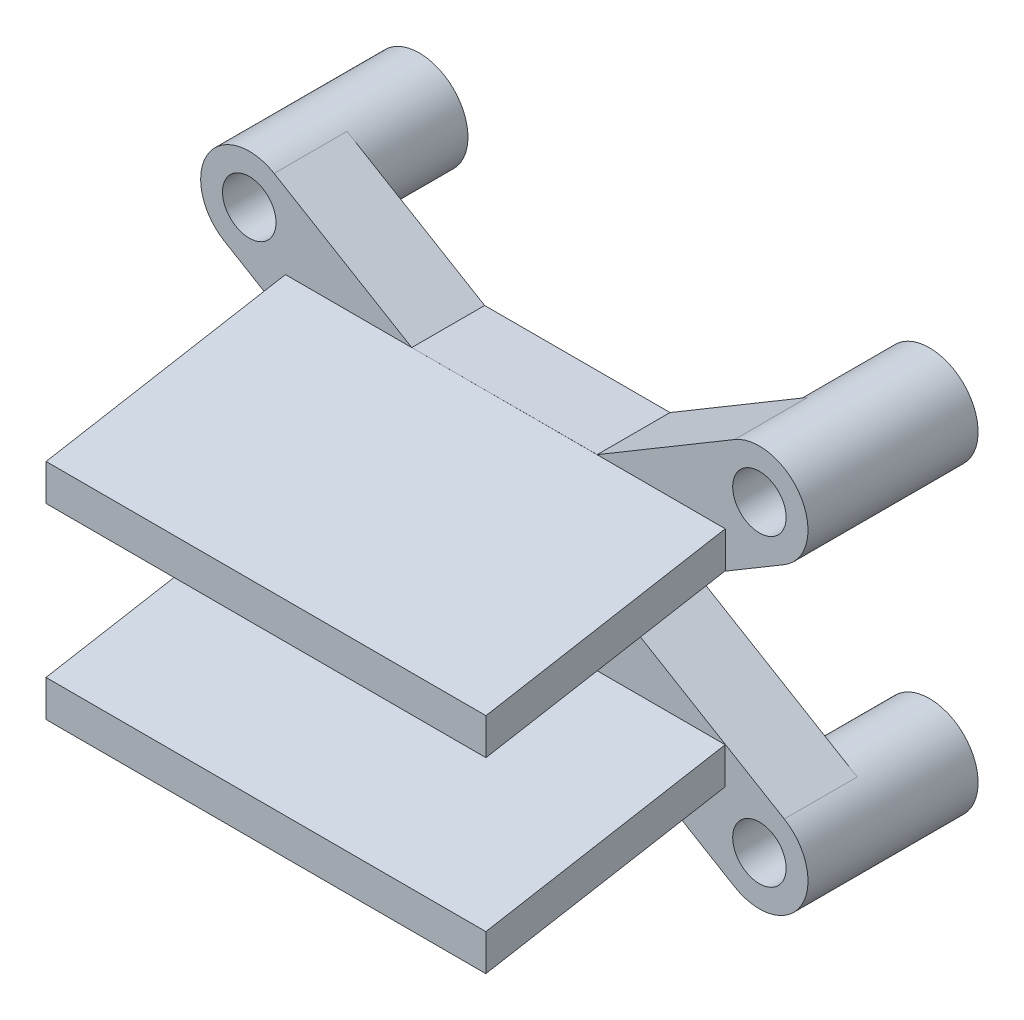
SolidWorks part; units mm, degrees
ref_plane "Alzado" through (0, 0, 0) normal (0, 0, 1) x (1, 0, 0)
ref_plane "Planta" through (0, 0, 0) normal (0, 1, 0) x (1, 0, 0)
ref_plane "Vista lateral" through (0, 0, 0) normal (1, 0, 0) x (0, 0, -1)
sketch "Croquis1" plane through (0, 0, 0) normal (0, 0, 1) x (1, 0, 0)
  line L0 (0, 0) -> (21, 0)
  line L1 (21, 0) -> (21, 12.5)
  line L2 (-1.023, 1.7186) -> (19.977, 14.2186)
  line L3 (1.0301, 14.2286) -> (22.0238, 1.7181)
  line L4 (22.023, 10.7814) -> (1.023, -1.7186)
  line L5 (19.9762, -1.7181) -> (-1.0176, 10.7924)
  circle A0 centre (0, 0) radius 2
  circle A1 centre (21, 12.5) radius 2
  circle A2 centre (21, 0) radius 2
  circle A3 centre (0.0063, 12.5105) radius 2
  circle A4 centre (0.0063, 12.5105) radius 1.1
  circle A5 centre (0, 0) radius 1.1
  circle A6 centre (21, 0) radius 1.1
  circle A7 centre (21, 12.5) radius 1.1
  dimension "D3" = 4
  dimension "D4" = 4
  dimension "D5" = 4
  dimension "D6" = 4
  dimension "D7" = 2.2
  dimension "D8" = 2.2
  dimension "D9" = 2.2
  dimension "D10" = 2.2
  dimension "D1" = 21
  dimension "D2" = 12.5
extrude "Saliente-Extruir1" add sketch "Croquis1" along normal blind 3
sketch "Croquis2" plane through (0, 0, 0) normal (0, 0, -1) x (-1, 0, 0)
  line L0 (-19.9762, -1.7181) -> (1.0176, 10.7924) construction
  line L1 (-22.023, 10.7814) -> (-1.023, -1.7186) construction
  line L2 (-1.0301, 14.2286) -> (-22.0238, 1.7181) construction
  line L3 (1.023, 1.7186) -> (-19.977, 14.2186) construction
  line L4 (0, 0) -> (-21, 0) construction
  line L5 (-21, 0) -> (-21, 12.5) construction
  line L6 (-19.9762, -1.7181) -> (1.0176, 10.7924)
  line L7 (-22.023, 10.7814) -> (-1.023, -1.7186)
  line L8 (-1.0301, 14.2286) -> (-22.0238, 1.7181)
  line L9 (1.023, 1.7186) -> (-19.977, 14.2186)
  line L10 (0, 0) -> (-21, 0)
  line L11 (-21, 0) -> (-21, 12.5)
  circle A1 centre (-0.0063, 12.5105) radius 2
  circle A2 centre (-0.0063, 12.5105) radius 2
  circle A3 centre (-21, 0) radius 2
  circle A4 centre (-21, 0) radius 2
  circle A5 centre (-21, 12.5) radius 2
  circle A6 centre (-21, 12.5) radius 2
  circle A7 centre (0, 0) radius 2
  circle A8 centre (0, 0) radius 2
  circle A9 centre (-21, 12.5) radius 1.1
  circle A10 centre (-21, 12.5) radius 1.1
  circle A11 centre (-21, 0) radius 1.1
  circle A12 centre (-21, 0) radius 1.1
  circle A13 centre (0, 0) radius 1.1
  circle A14 centre (0, 0) radius 1.1
  circle A15 centre (-0.0063, 12.5105) radius 1.1
  circle A16 centre (-0.0063, 12.5105) radius 1.1
  dimension "D1" = 0
  dimension "D2" = 0
  dimension "D3" = 0
  dimension "D4" = 0
  dimension "D5" = 0
  dimension "D6" = 0
  dimension "D7" = 0
  dimension "D8" = 0
extrude "Saliente-Extruir2" add sketch "Croquis2" along normal blind 4
sketch "Croquis3" plane through (0, 0, 3) normal (0, 0, 1) x (1, 0, 0)
  line L0 (19.9762, -1.7181) -> (-1.0176, 10.7924) construction
  line L1 (22.023, 10.7814) -> (1.023, -1.7186) construction
  line L2 (1.0301, 14.2286) -> (22.0238, 1.7181) construction
  line L3 (-1.023, 1.7186) -> (19.977, 14.2186) construction
  line L4 (0, 0) -> (21, 0) construction
  line L5 (21, 0) -> (21, 12.5) construction
  line L6 (19.9762, -1.7181) -> (-1.0176, 10.7924)
  line L7 (22.023, 10.7814) -> (1.023, -1.7186)
  line L8 (1.0301, 14.2286) -> (22.0238, 1.7181)
  line L9 (-1.023, 1.7186) -> (19.977, 14.2186)
  line L10 (0, 0) -> (21, 0)
  line L11 (21, 0) -> (21, 12.5)
  line L12 (14.4145, 6.2526) -> (6.5974, 6.2545) construction
  line L13 (6.5974, 6.2545) -> (10.506, 6.2536) construction
  line L14 (10.506, 6.2536) -> (10.506, 9.3536) construction
  line L15 (9.2082, 9.3536) -> (11.8038, 9.3536)
  line L16 (10.506, 6.2536) -> (10.506, 10.8536) construction
  line L17 (6.6882, 10.8536) -> (14.3238, 10.8536)
  line L18 (9.2066, 3.1542) -> (11.8022, 3.1529)
  line L19 (6.6859, 1.6555) -> (14.3215, 1.6516)
  line L20 (9.2066, 3.1542) -> (11.8022, 3.1529)
  line L21 (6.6859, 1.6555) -> (14.3215, 1.6516)
  line L22 (9.2082, 9.3536) -> (1.7082, 9.3536)
  line L23 (1.7082, 9.3536) -> (1.7082, 10.7924)
  line L24 (1.7082, 10.7924) -> (6.6882, 10.8536)
  line L25 (11.8038, 9.3536) -> (19.3038, 9.3536)
  line L26 (19.3038, 9.3536) -> (19.3038, 10.7924)
  line L27 (19.3038, 10.7924) -> (14.3238, 10.8536)
  line L28 (9.2066, 3.1542) -> (11.8022, 3.1529)
  line L29 (9.2066, 3.1542) -> (1.7066, 3.158)
  line L30 (1.7066, 3.158) -> (1.7059, 1.7191)
  line L31 (1.7059, 1.7191) -> (6.6859, 1.6555)
  line L32 (6.6859, 1.6555) -> (14.3215, 1.6516)
  line L33 (19.3015, 1.7103) -> (14.3215, 1.6516)
  line L34 (19.3022, 3.1492) -> (19.3015, 1.7103)
  line L35 (11.8022, 3.1529) -> (19.3022, 3.1492)
  circle A1 centre (0.0063, 12.5105) radius 2
  circle A2 centre (0.0063, 12.5105) radius 2
  circle A3 centre (21, 0) radius 2
  circle A4 centre (21, 0) radius 2
  circle A5 centre (21, 12.5) radius 2
  circle A6 centre (21, 12.5) radius 2
  circle A7 centre (0, 0) radius 2
  circle A8 centre (0, 0) radius 2
  circle A9 centre (21, 12.5) radius 1.1
  circle A10 centre (21, 12.5) radius 1.1
  circle A11 centre (21, 0) radius 1.1
  circle A12 centre (21, 0) radius 1.1
  circle A13 centre (0, 0) radius 1.1
  circle A14 centre (0, 0) radius 1.1
  circle A15 centre (0.0063, 12.5105) radius 1.1
  circle A16 centre (0.0063, 12.5105) radius 1.1
  point P41 (10.506, 9.3536)
  point P45 (10.506, 10.8536)
  line M29 (1.023, -1.7186) -> (10.5054, 3.9257)
  dimension "D9" = 3.1
  dimension "D10" = 4.6
  dimension "D11" = 7.5
  dimension "D1" = 0
  dimension "D2" = 0
  dimension "D3" = 0
  dimension "D4" = 0
  dimension "D5" = 0
  dimension "D6" = 0
  dimension "D7" = 0
  dimension "D8" = 0
extrude "Saliente-Extruir3" add sketch "Croquis3" against normal blind 3 contours L24 L23 L22 L15 L8 L17 | L17 L8 L15 L9 | L26 L27 L9 L25 | L30 L31 L19 L18 L29 M29 | L19 L6 L18 M29 | L35 L6 L33 L34
ref_plane "Plano1" through (6.6914, 1.6555, 0) normal (1, -0.0005, 0) x (0, 0, -1)
sketch "Croquis5" plane through (6.6914, 1.6555, 0) normal (1, -0.0005, 0) x (0, 0, -1)
  line L0 (-3, 0) -> (0, 0) construction
  line L1 (-3, 0) -> (0, 0)
  line L2 (-3, 1.5) -> (0, 1.5) construction
  line L3 (-3, 1.5) -> (0, 1.5)
  line L4 (-3, 0) -> (-12.8481, -1.7365)
  line L5 (-3, 1.5) -> (-12.8481, -0.2365)
  line L6 (-3, 1.5) -> (-3, 0)
  line L7 (-12.8481, 7.4616) -> (-12.8481, 5.9629)
  line L8 (-3, 9.1981) -> (0, 9.1981) construction
  line L9 (0, 7.6994) -> (-3, 7.6994) construction
  line L10 (-3, 9.1981) -> (0, 9.1981)
  line L11 (0, 7.6994) -> (-3, 7.6994)
  line L12 (-3, 7.6994) -> (-12.8481, 5.9629)
  line L13 (-3, 9.1981) -> (-12.8481, 7.4616)
  line L14 (-12.8481, -0.2365) -> (-12.8481, -1.7365)
  line L15 (-3, 9.1981) -> (-3, 7.6994)
extrude "Saliente-Extruir4" add sketch "Croquis5" along normal blind 12.9 and the other way blind 5.2
